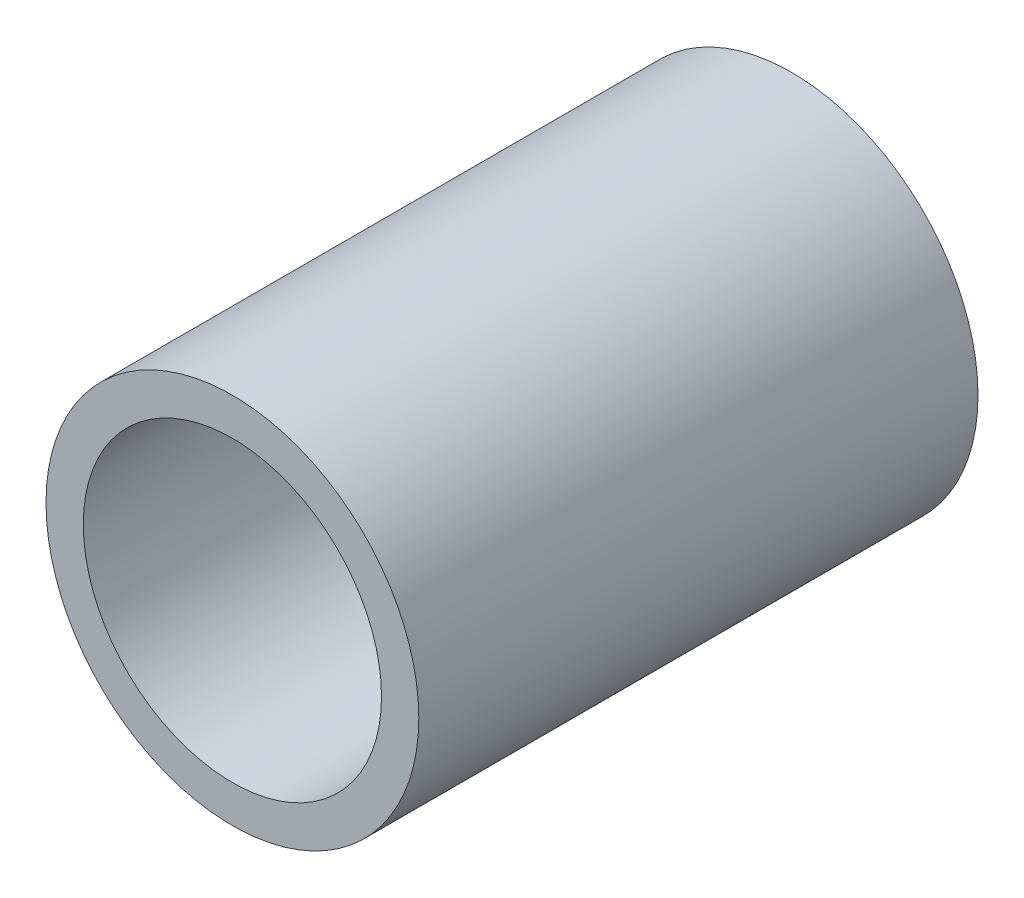
SolidWorks part; units mm, degrees
ref_plane "Plan de face" through (0, 0, 0) normal (1, 0, 0) x (0, 1, 0)
ref_plane "Plan de dessus" through (0, 0, 0) normal (0, 0, 1) x (0, 1, 0)
ref_plane "Plan de droite" through (0, 0, 0) normal (0, 1, 0) x (-1, 0, 0)
sketch "Esquisse1" plane through (0, 0, 0) normal (0, 0, 1) x (0, 1, 0)
  circle A0 centre (0, 0) radius 4
  circle A1 centre (0, 0) radius 5
  dimension "D1" = 10
  dimension "D2" = 8
extrude "Boss.-Extru.1" add sketch "Esquisse1" along normal blind 15
